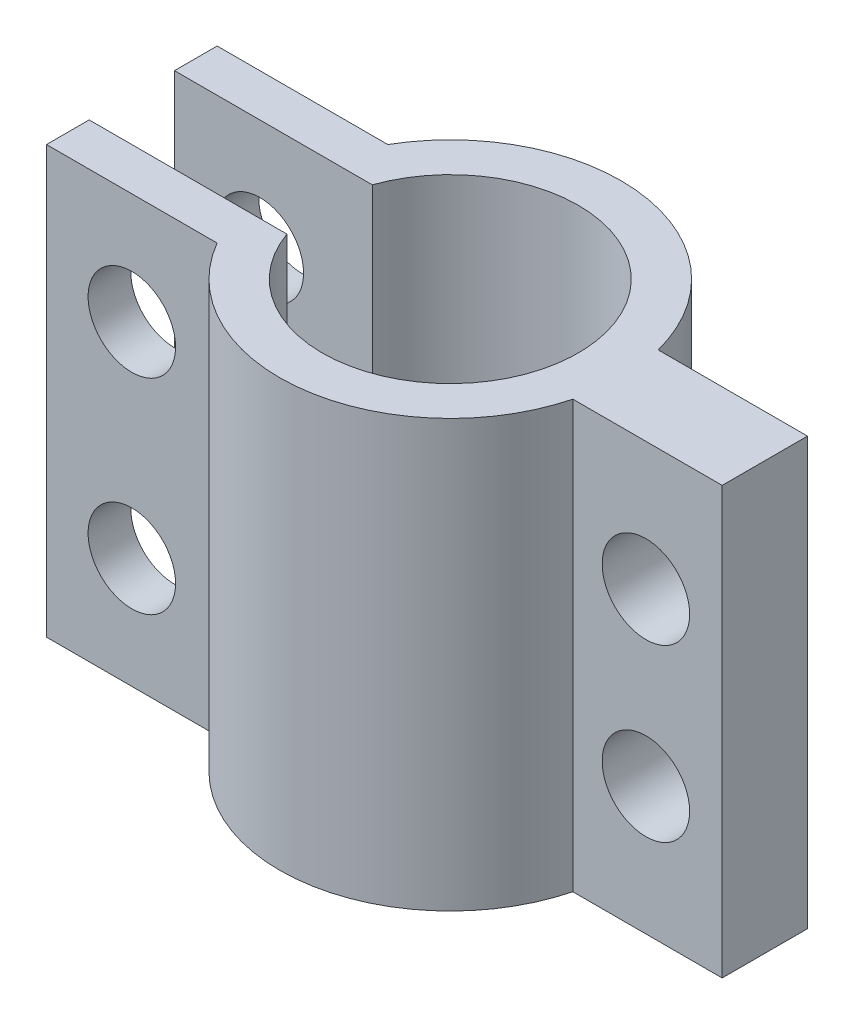
SolidWorks part; units mm, degrees
ref_plane "Front Plane" through (0, 0, 0) normal (0, 0, 1) x (1, 0, 0)
ref_plane "Top Plane" through (0, 0, 0) normal (0, 1, 0) x (1, 0, 0)
ref_plane "Right Plane" through (0, 0, 0) normal (1, 0, 0) x (0, 0, -1)
sketch "Sketch1" plane through (0, 0, 0) normal (0, 1, 0) x (1, 0, 0)
  line L0 (0, 0) -> (-12.1528, 0) construction
  line L1 (-5.6569, 2) -> (-14.9282, 2)
  line L2 (-14.9282, 2) -> (-14.9282, 4)
  line L3 (-14.9282, 4) -> (-6.9282, 4)
  line L4 (-14.9282, -4) -> (-6.9282, -4)
  line L5 (-14.9282, -2) -> (-14.9282, -4)
  line L6 (-5.6569, -2) -> (-14.9282, -2)
  line L7 (7.746, 2) -> (14.746, 2)
  line L8 (14.746, 2) -> (14.746, -2)
  line L9 (14.746, -2) -> (7.746, -2)
  circle A0 centre (0, 0) radius 6 construction
  circle A1 centre (0, 0) radius 8 construction
  arc A2 (-5.6569, 2) -> (-5.6569, -2) centre (0, 0) cw
  arc A3 (-6.9282, 4) -> (-6.9282, -4) centre (0, 0) cw
  dimension "D1" = 12
  dimension "D2" = 2
  dimension "D3" = 2
  dimension "D4" = 2
  dimension "D5" = 4
  dimension "6" = 8
  dimension "D6" = 7
extrude "Boss-Extrude1" add sketch "Sketch1" along normal blind 20 contours L7 A3 L9 L8
sketch "Sketch2" plane through (0, 0, 4) normal (0, 0, 1) x (1, 0, 0)
  line L0 (-6.9282, 20) -> (-6.9282, 0) construction
  line L1 (-6.9282, 10) -> (-19.4184, 10) construction
  circle A0 centre (-10.9282, 14.8) radius 2.05
  circle A1 centre (-10.9282, 5.2) radius 2.05
  circle A2 centre (11.1707, 14) radius 2.05
  circle A3 centre (11.1707, 6) radius 2.05
  point P4 (0, 0)
  point P13 (0, 0)
  dimension "D1" = 4.1
  dimension "D2" = 4.1
  dimension "D3" = 4
  dimension "D4" = 4.8
  dimension "D5" = 4
extrude "Cut-Extrude1" cut sketch "Sketch2" against normal blind 20
